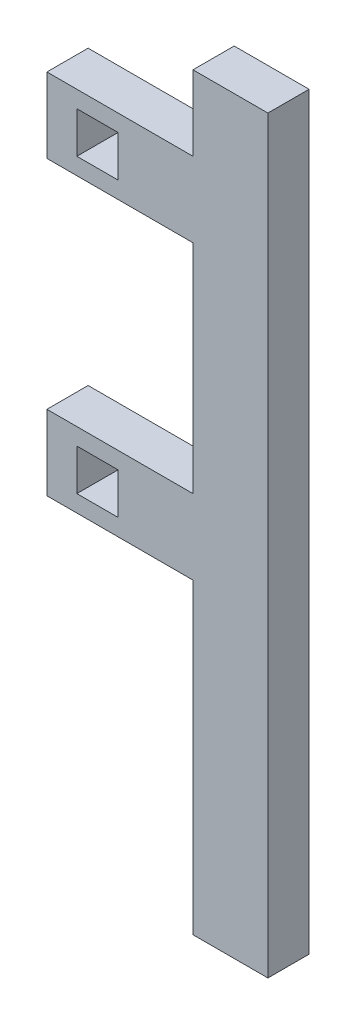
SolidWorks part; units mm, degrees
material "ﾁｰｸ材"
ref_plane "正面" through (0, 0, 0) normal (0, 0, 1) x (1, 0, 0)
ref_plane "平面" through (0, 0, 0) normal (0, 1, 0) x (1, 0, 0)
ref_plane "右側面" through (0, 0, 0) normal (1, 0, 0) x (0, 0, -1)
sketch "ｽｹｯﾁ1" plane through (0, 0, 0) normal (0, 0, 1) x (1, 0, 0)
  line L0 (-6.75, 5) -> (-6.75, -5)
  line L1 (-2.75, 2.75) -> (2.75, 2.75)
  line L2 (-2.75, 2.75) -> (-2.75, -2.75)
  line L3 (-2.75, -2.75) -> (2.75, -2.75)
  line L4 (2.75, 2.75) -> (2.75, -2.75)
  line L5 (-2.75, 2.75) -> (2.75, -2.75) construction
  line L6 (-2.75, -2.75) -> (2.75, 2.75) construction
  line L7 (-6.75, -5) -> (12.75, -5)
  line L8 (12.75, -5) -> (12.75, -46)
  line L9 (12.75, -46) -> (22.75, -46)
  line L10 (22.75, -46) -> (22.75, 54)
  line L11 (22.75, 54) -> (12.75, 54)
  line L12 (12.75, 54) -> (12.75, 44)
  line L13 (12.75, 5) -> (-6.75, 5)
  line L14 (12.75, 44) -> (-6.75, 44)
  line L15 (-6.75, 44) -> (-6.75, 34)
  line L16 (-6.75, 34) -> (12.75, 34)
  line L17 (12.75, 34) -> (12.75, 5)
  line L18 (-2.75, 41.75) -> (2.75, 41.75)
  line L19 (-2.75, 41.75) -> (-2.75, 36.25)
  line L20 (-2.75, 36.25) -> (2.75, 36.25)
  line L21 (2.75, 41.75) -> (2.75, 36.25)
  line L22 (-2.75, 41.75) -> (2.75, 36.25) construction
  line L23 (-2.75, 36.25) -> (2.75, 41.75) construction
  point P0 (0, 0)
  point P14 (-6.75, 0)
  point P19 (0, 39)
  point P25 (-6.75, 39)
  point P26 (-2.75, 39)
  dimension "D1" = 5.5
  dimension "D2" = 5.5
  dimension "D3" = 10
  dimension "D4" = 10
  dimension "D5" = 4
  dimension "D6" = 100
  dimension "D7" = 10
  dimension "D8" = 41
  dimension "D9" = 10
  dimension "D10" = 10
  dimension "D11" = 5.5
  dimension "D12" = 5.5
extrude "ﾎﾞｽ - 押し出し1" add sketch "ｽｹｯﾁ1" along normal blind 5.5
sketch "ｽｹｯﾁ3" plane through (22.75, 0, 0) normal (1, 0, 0) x (0, 0, -1)
  line L0 (-5.5, 4) -> (0, 4) construction
  line L1 (-5.5, -46) -> (-5.5, 54) construction
  line L2 (0, -46) -> (0, 54) construction
